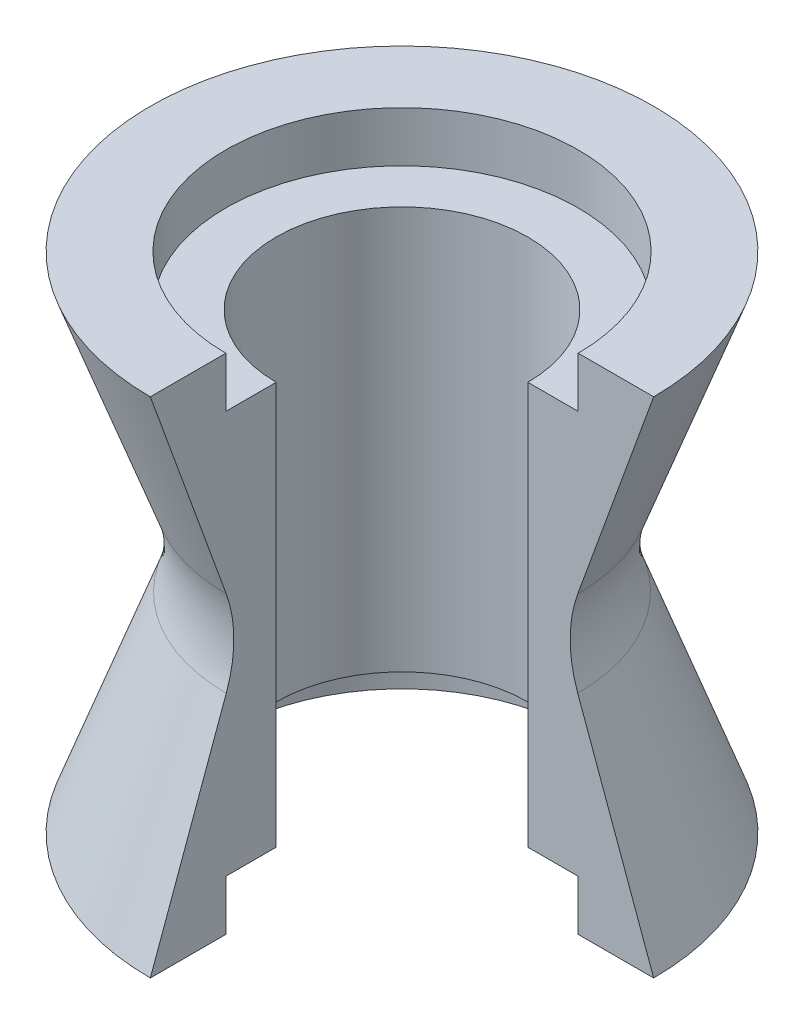
SolidWorks part; units mm, degrees
material "Plain Carbon Steel"
ref_plane "Front Plane" through (0, 0, 0) normal (0, 0, 1) x (1, 0, 0)
ref_plane "Top Plane" through (0, 0, 0) normal (0, 1, 0) x (1, 0, 0)
ref_plane "Right Plane" through (0, 0, 0) normal (1, 0, 0) x (0, 0, -1)
sketch "Sketch1" plane through (0, 0, 0) normal (0, 1, 0) x (1, 0, 0)
  circle A0 centre (0, 0) radius 50
  dimension "D1" = 100
extrude "Boss-Extrude1" add sketch "Sketch1" along normal blind 50 draft 20
mirror "Mirror1" [suppressed] about plane through (0, 0, 0) normal (0, 1, 0)
mirror "Mirror2" about plane through (0, 50, 0) normal (0, 1, 0) of "Boss-Extrude1"
sketch "Sketch2" plane through (0, 100, 0) normal (0, 1, 0) x (1, 0, 0)
  circle A3 centre (0, 0) radius 25
  dimension "D1" = 50
extrude "Cut-Extrude1" cut sketch "Sketch2" against normal through all both and the other way through all
sketch "Sketch3" plane through (0, 100, 0) normal (0, 1, 0) x (1, 0, 0)
  circle A0 centre (0, 0) radius 35
  dimension "D1" = 70
extrude "Cut-Extrude2" cut sketch "Sketch3" against normal blind 10
sketch "Sketch5" plane through (0, 0, 0) normal (0, -1, 0) x (1, 0, 0)
  circle A0 centre (0, 0) radius 35
  circle A2 centre (0, 0) radius 35 construction
extrude "Cut-Extrude5" cut sketch "Sketch5" against normal blind 10
fillet "Fillet1" radius 25 1 edges at (0, 50, 31.8015)
sketch "Sketch7" plane through (0, 100, 0) normal (0, 1, 0) x (1, 0, 0)
  line L0 (0, -50) -> (0, 0)
  line L1 (0, 0) -> (50, 0)
  circle A0 centre (0, 0) radius 50 construction
  arc A1 (0, -50) -> (50, 0) centre (0, 0) ccw
extrude "Cut-Extrude6" cut sketch "Sketch7" against normal through all both and the other way through all
equation "\"A\"= 100"
equation "\"B\"= 100"
equation "\"C\"= 20"
equation "\"D3@Boss-Extrude1\"=\"C\""
equation "\"D1@Sketch1\"=\"B\""
equation "\"D1@Boss-Extrude1\"=\"A\"/2"
